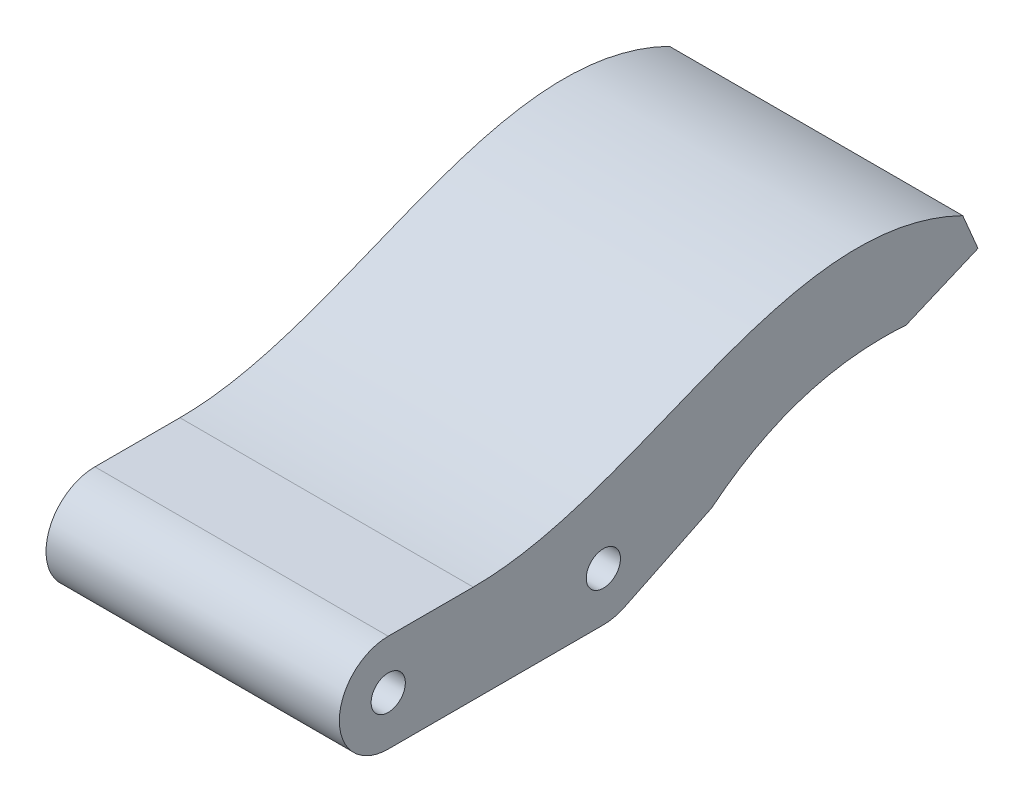
SolidWorks part; units mm, degrees
ref_plane "Front Plane" through (0, 0, 0) normal (0, 0, 1) x (1, 0, 0)
ref_plane "Top Plane" through (0, 0, 0) normal (0, 1, 0) x (1, 0, 0)
ref_plane "Right Plane" through (0, 0, 0) normal (1, 0, 0) x (0, 0, -1)
sketch "Sketch1" plane through (0, 0, 0) normal (1, 0, 0) x (0, 0, -1)
  line L1 (0, 0) -> (27, 0)
  line L2 (0, 0) -> (0, 10)
  line L3 (0, 10) -> (27, 10)
  circle A0 centre (5, 5) radius 1.75
  circle A1 centre (5, 5) radius 5
  circle A2 centre (27, 5) radius 5
  circle A3 centre (27, 5) radius 1.75
  dimension "D7" = 3.5
  dimension "D11" = 10
  dimension "D2" = 3.5
  dimension "D1" = 10
  dimension "D8" = 5
  dimension "D9" = 5
  dimension "D10" = 22
extrude "Boss-Extrude1" add sketch "Sketch1" along normal blind 30 contours A1 A0 | A2 L3 A1 L1 | A2 A3 | L2 A1 | L1 A1
sketch "Sketch2" plane through (30, 0, 0) normal (1, 0, 0) x (0, 0, -1)
  line L6 (5, 10) -> (27, 10) construction
  line L14 (5, 10) -> (27, 10)
  line L20 (29.1838, 0.5021) -> (38.0854, 4.8241)
  line L21 (57.948, 11.0678) -> (65.3138, 14.1895)
  line L22 (65.3138, 14.1895) -> (63.753, 17.8724)
  arc A3 (27, 0) -> (27, 10) centre (27, 5) ccw construction
  arc A4 (27, 0) -> (27, 10) centre (27, 5) ccw
  spline S0 degree 2 poles (38.0854, 4.8241) (46.7975, 11.8952) (57.948, 11.0678) knots 0 0 0 1 1 1
  spline S1 degree 3 poles (63.753, 17.8724) (45.9289, 26.5638) (31.0593, 10) (13.695, 10) knots 0 0 0 0 1 1 1 1
  point P2 (27, 5)
  dimension "D3" = 4
  dimension "D4" = 8
extrude "Boss-Extrude2" add sketch "Sketch2" against normal up to surface (30 mm away) up to face at (0, 5, -16)
